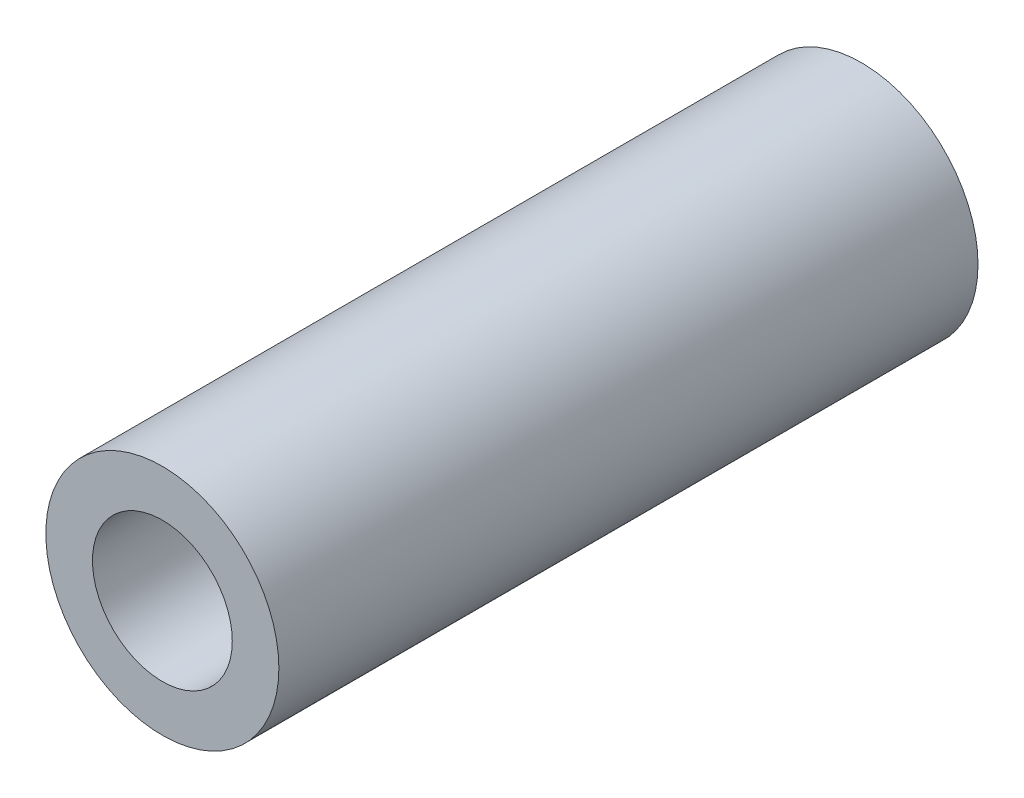
SolidWorks part; units mm, degrees
ref_plane "Alzado" through (0, 0, 0) normal (0, 0, 1) x (1, 0, 0)
ref_plane "Planta" through (0, 0, 0) normal (0, 1, 0) x (1, 0, 0)
ref_plane "Vista lateral" through (0, 0, 0) normal (1, 0, 0) x (0, 0, -1)
sketch "Croquis1" plane through (0, 0, 0) normal (0, 0, 1) x (1, 0, 0)
  circle A0 centre (0, 0) radius 1.5
  circle A1 centre (0, 0) radius 2.5
  dimension "D1" = 3
  dimension "D2" = 5
extrude "Saliente-Extruir1" add sketch "Croquis1" along normal blind 15
